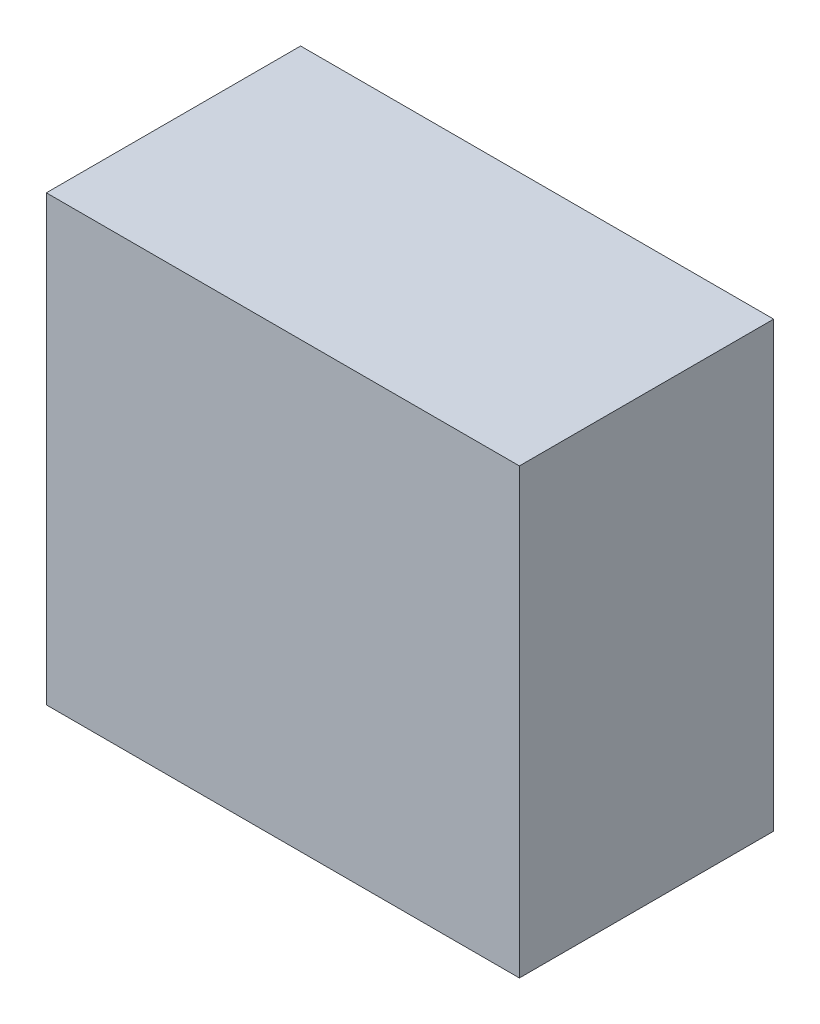
SolidWorks part; units mm, degrees
ref_plane "Front Plane" through (0, 0, 0) normal (0, 0, 1) x (1, 0, 0)
ref_plane "Top Plane" through (0, 0, 0) normal (0, 1, 0) x (1, 0, 0)
ref_plane "Right Plane" through (0, 0, 0) normal (1, 0, 0) x (0, 0, -1)
sketch "Sketch1" plane through (0, 0, 0) normal (0, 1, 0) x (1, 0, 0)
  line L1 (-160, -86) -> (160, -86)
  line L2 (-160, -86) -> (-160, 86)
  line L3 (-160, 86) -> (160, 86)
  line L4 (160, -86) -> (160, 86)
  line L5 (-160, -86) -> (160, 86) construction
  line L6 (-160, 86) -> (160, -86) construction
  point P0 (0, 0)
  dimension "D1" = 172
  dimension "D2" = 320
extrude "Boss-Extrude1" add sketch "Sketch1" along normal blind 300
